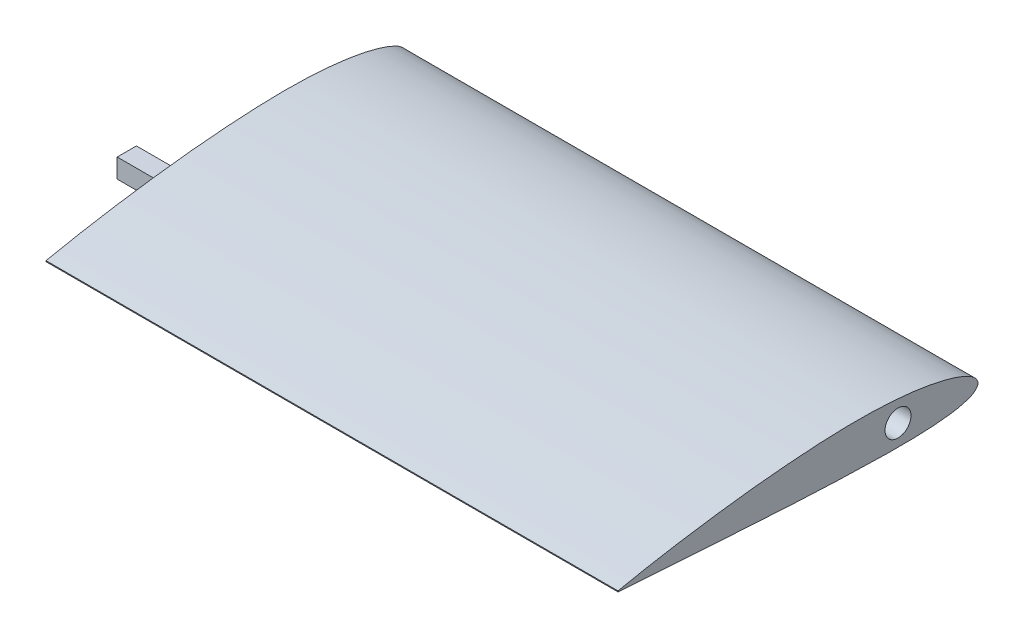
SolidWorks part; units mm, degrees
ref_plane "Front Plane" through (0, 0, 0) normal (0, 0, 1) x (1, 0, 0)
ref_plane "Top Plane" through (0, 0, 0) normal (0, 1, 0) x (1, 0, 0)
ref_plane "Right Plane" through (0, 0, 0) normal (1, 0, 0) x (0, 0, -1)
sketch "Sketch4" plane through (0, 0, 0) normal (0, 0, 1) x (1, 0, 0)
  line L0 (-30.3109, 17.5) -> (30.3109, 17.5)
  arc A1 (30.3109, 17.5) -> (-30.3109, 17.5) centre (0, 0) ccw
  dimension "D1" = 35
  dimension "D2" = 17.5
extrude "Exterior" add sketch "Sketch4" along normal blind 90 contours L0 A1
sketch "Sketch5" plane through (0, 0, 0) normal (0, 0, -1) x (-1, 0, 0)
  line L0 (30.3109, 17.5) -> (-30.3109, 17.5) construction
  line L1 (23.1247, 17.5) -> (-23.1247, 17.5)
  arc A0 (23.1247, 17.5) -> (-23.1247, 17.5) centre (0, 0) ccw
  dimension "D1" = 58
extrude "Boss-Extrude1" add sketch "Sketch5" along normal blind 15
curve "Curve3"
  spline degree 3 poles (0, 1.3, 1000) (0, 4.7133, 983.3426) (0, 11.531, 950.0715) (0, 24.0186, 883.4722) (0, 37.8548, 800.1781) (0, 52.175, 700.1592) (0, 64.1175, 600.1567) (0, 72.8619, 500.1109) (0, 78.7837, 400.0878) (0, 79.786, 316.6355) (0, 77.0249, 249.9395) (0, 72.979, 199.8766) (0, 66.5721, 149.7505) (0, 58.6825, 108.0331) (0, 49.7566, 74.7751) (0, 41.6416, 49.5609) (0, 32.1864, 28.1982) (0, 20.723, 9.771) (0, 0.8988, -6.2982) (0, -16.5264, 10.3934) (0, -24.4739, 28.476) (0, -30.5108, 49.7447) (0, -34.8393, 74.8759) (0, -38.5332, 108.2669) (0, -41.3764, 149.947) (0, -42.5163, 199.9941) (0, -42.3574, 250.0055) (0, -40.8857, 316.6783) (0, -38.2375, 400.0272) (0, -33.6287, 500.0334) (0, -27.6385, 600.0106) (0, -21.4122, 700.0048) (0, -15.1098, 800.0161) (0, -9.3053, 883.3314) (0, -4.8282, 950.0042) (0, -2.4761, 983.334) (0, -1.3, 1000) knots 0 0 0 0 0.025012 0.049959 0.099673 0.149206 0.198581 0.247805 0.296917 0.345953 0.370492 0.395091 0.419815 0.444799 0.45749 0.470406 0.483879 0.491264 0.503459 0.513609 0.520451 0.533235 0.545691 0.558032 0.582609 0.607135 0.631652 0.656174 0.705234 0.75432 0.803437 0.852566 0.901701 0.950849 0.975423 1 1 1 1
sketch "Sketch7" plane through (0, 0, 0) normal (1, 0, 0) x (0, 0, -1)
  line L0 (-90, 21.4324) -> (-90, 21.1984)
  line L1 (-90, 21.3154) -> (0, 21.434) construction
  line L2 (0, 21.434) -> (-0.0572, 64.8516) construction
  line L7 (-90, 17.5) -> (0, 17.5) construction
  line L9 (0, 17.5) -> (0, 29) construction
  spline S1 degree 3 poles (-90, 21.4324) (-88.5009, 21.7395) (-85.5067, 22.3531) (-79.5132, 23.4769) (-72.0173, 24.7221) (-63.0162, 26.0108) (-54.0165, 27.0856) (-45.013, 27.8725) (-36.0116, 28.4054) (-28.5014, 28.4956) (-22.4991, 28.2471) (-17.9938, 27.883) (-13.4827, 27.3065) (-9.7284, 26.5964) (-6.7354, 25.7932) (-4.4663, 25.0629) (-2.5438, 24.212) (-0.8854, 23.1803) (0.5607, 21.3963) (-0.9415, 19.8281) (-2.5688, 19.1129) (-4.4828, 18.5696) (-6.7445, 18.18) (-9.7495, 17.8476) (-13.5004, 17.5918) (-18.0044, 17.4892) (-22.5051, 17.5035) (-28.5052, 17.6359) (-36.0061, 17.8742) (-45.0061, 18.289) (-54.0034, 18.8281) (-63.0023, 19.3884) (-72.0027, 19.9556) (-79.5005, 20.478) (-85.5007, 20.8809) (-88.5002, 21.0925) (-90, 21.1984) knots 0 0 0 0 0.025012 0.049959 0.099673 0.149206 0.198581 0.247805 0.296917 0.345953 0.370492 0.395091 0.419815 0.444799 0.45749 0.470406 0.483879 0.491264 0.503459 0.513609 0.520451 0.533235 0.545691 0.558032 0.582609 0.607135 0.631652 0.656174 0.705234 0.75432 0.803437 0.852566 0.901701 0.950849 0.975423 1 1 1 1
  dimension "D1" = 90
ref_plane "Plane1" through (80, 0, 0) normal (1, 0, 0) x (0, 0, -1)
ref_plane "Plane2" through (-80, 0, 0) normal (1, 0, 0) x (0, 0, -1)
sketch "Sketch8" plane through (80, 0, 0) normal (1, 0, 0) x (0, 0, -1)
  line L0 (-90, 21.4324) -> (-90, 21.1984)
  spline S0 degree 3 poles (-716.115, 1915.3026) (-242.1094, -47.4437) (-166.1672, 7.229) (-79.5132, 23.4769) (-72.0173, 24.7221) (-63.0162, 26.0108) (-54.0165, 27.0856) (-45.013, 27.8725) (-36.0116, 28.4054) (-28.5014, 28.4956) (-22.4991, 28.2471) (-17.9938, 27.883) (-13.4827, 27.3065) (-9.7284, 26.5964) (-6.7354, 25.7932) (-4.4663, 25.0629) (-2.5438, 24.212) (-0.8854, 23.1803) (0.5607, 21.3963) (-0.9415, 19.8281) (-2.5688, 19.1129) (-4.4828, 18.5696) (-6.7445, 18.18) (-9.7495, 17.8476) (-13.5004, 17.5918) (-18.0044, 17.4892) (-22.5051, 17.5035) (-28.5052, 17.6359) (-36.0061, 17.8742) (-45.0061, 18.289) (-54.0034, 18.8281) (-63.0023, 19.3884) (-72.0027, 19.9556) (-79.5005, 20.478) (-222.3619, 30.0711) (-360.6967, 61.6518) (-633.8387, -1888.1939) knots -1.34139 -1.34139 -1.34139 -1.34139 0.025012 0.049959 0.099673 0.149206 0.198581 0.247805 0.296917 0.345953 0.370492 0.395091 0.419815 0.444799 0.45749 0.470406 0.483879 0.491264 0.503459 0.513609 0.520451 0.533235 0.545691 0.558032 0.582609 0.607135 0.631652 0.656174 0.705234 0.75432 0.803437 0.852566 0.901701 0.950849 0.975423 3.242166 3.242166 3.242166 3.242166 only from (-90, 21.4324) to (-90, 21.1984) construction
  spline S1 degree 3 poles (-90, 21.4324) (-88.5009, 21.7395) (-85.5067, 22.3531) (-79.5132, 23.4769) (-72.0173, 24.7221) (-63.0162, 26.0108) (-54.0165, 27.0856) (-45.013, 27.8725) (-36.0116, 28.4054) (-28.5014, 28.4956) (-22.4991, 28.2471) (-17.9938, 27.883) (-13.4827, 27.3065) (-9.7284, 26.5964) (-6.7354, 25.7932) (-4.4663, 25.0629) (-2.5438, 24.212) (-0.8854, 23.1803) (0.5607, 21.3963) (-0.9415, 19.8281) (-2.5688, 19.1129) (-4.4828, 18.5696) (-6.7445, 18.18) (-9.7495, 17.8476) (-13.5004, 17.5918) (-18.0044, 17.4892) (-22.5051, 17.5035) (-28.5052, 17.6359) (-36.0061, 17.8742) (-45.0061, 18.289) (-54.0034, 18.8281) (-63.0023, 19.3884) (-72.0027, 19.9556) (-79.5005, 20.478) (-85.5007, 20.8809) (-88.5002, 21.0925) (-90, 21.1984) knots 0 0 0 0 0.025012 0.049959 0.099673 0.149206 0.198581 0.247805 0.296917 0.345953 0.370492 0.395091 0.419815 0.444799 0.45749 0.470406 0.483879 0.491264 0.503459 0.513609 0.520451 0.533235 0.545691 0.558032 0.582609 0.607135 0.631652 0.656174 0.705234 0.75432 0.803437 0.852566 0.901701 0.950849 0.975423 1 1 1 1
sketch "Sketch9" plane through (-80, 0, 0) normal (1, 0, 0) x (0, 0, -1)
  line L0 (-90, 21.4324) -> (-90, 21.1984)
  spline S0 degree 3 poles (-716.115, 1915.3026) (-242.1094, -47.4437) (-166.1672, 7.229) (-79.5132, 23.4769) (-72.0173, 24.7221) (-63.0162, 26.0108) (-54.0165, 27.0856) (-45.013, 27.8725) (-36.0116, 28.4054) (-28.5014, 28.4956) (-22.4991, 28.2471) (-17.9938, 27.883) (-13.4827, 27.3065) (-9.7284, 26.5964) (-6.7354, 25.7932) (-4.4663, 25.0629) (-2.5438, 24.212) (-0.8854, 23.1803) (0.5607, 21.3963) (-0.9415, 19.8281) (-2.5688, 19.1129) (-4.4828, 18.5696) (-6.7445, 18.18) (-9.7495, 17.8476) (-13.5004, 17.5918) (-18.0044, 17.4892) (-22.5051, 17.5035) (-28.5052, 17.6359) (-36.0061, 17.8742) (-45.0061, 18.289) (-54.0034, 18.8281) (-63.0023, 19.3884) (-72.0027, 19.9556) (-79.5005, 20.478) (-222.3619, 30.0711) (-360.6967, 61.6518) (-633.8387, -1888.1939) knots -1.34139 -1.34139 -1.34139 -1.34139 0.025012 0.049959 0.099673 0.149206 0.198581 0.247805 0.296917 0.345953 0.370492 0.395091 0.419815 0.444799 0.45749 0.470406 0.483879 0.491264 0.503459 0.513609 0.520451 0.533235 0.545691 0.558032 0.582609 0.607135 0.631652 0.656174 0.705234 0.75432 0.803437 0.852566 0.901701 0.950849 0.975423 3.242166 3.242166 3.242166 3.242166 only from (-90, 21.4324) to (-90, 21.1984) construction
  spline S1 degree 3 poles (-90, 21.4324) (-88.5009, 21.7395) (-85.5067, 22.3531) (-79.5132, 23.4769) (-72.0173, 24.7221) (-63.0162, 26.0108) (-54.0165, 27.0856) (-45.013, 27.8725) (-36.0116, 28.4054) (-28.5014, 28.4956) (-22.4991, 28.2471) (-17.9938, 27.883) (-13.4827, 27.3065) (-9.7284, 26.5964) (-6.7354, 25.7932) (-4.4663, 25.0629) (-2.5438, 24.212) (-0.8854, 23.1803) (0.5607, 21.3963) (-0.9415, 19.8281) (-2.5688, 19.1129) (-4.4828, 18.5696) (-6.7445, 18.18) (-9.7495, 17.8476) (-13.5004, 17.5918) (-18.0044, 17.4892) (-22.5051, 17.5035) (-28.5052, 17.6359) (-36.0061, 17.8742) (-45.0061, 18.289) (-54.0034, 18.8281) (-63.0023, 19.3884) (-72.0027, 19.9556) (-79.5005, 20.478) (-85.5007, 20.8809) (-88.5002, 21.0925) (-90, 21.1984) knots 0 0 0 0 0.025012 0.049959 0.099673 0.149206 0.198581 0.247805 0.296917 0.345953 0.370492 0.395091 0.419815 0.444799 0.45749 0.470406 0.483879 0.491264 0.503459 0.513609 0.520451 0.533235 0.545691 0.558032 0.582609 0.607135 0.631652 0.656174 0.705234 0.75432 0.803437 0.852566 0.901701 0.950849 0.975423 1 1 1 1
loft "Loft9" add profiles "Sketch8", "Sketch9"
sketch "Sketch12" plane through (80, 0, 0) normal (1, 0, 0) x (0, 0, -1)
  line L0 (-90, 21.4324) -> (-90, 21.1984) construction
  line L1 (-90, 21.4324) -> (-90, 21.1984)
  line L2 (-90, 21.4324) -> (-97.2409, 26.9065)
  line L3 (-97.2409, 26.9065) -> (-90.2923, 42.7722)
  line L4 (-90.2923, 42.7722) -> (-30.1138, 44.0233)
  line L5 (-30.1138, 44.0233) -> (6.4186, 38.5184)
  line L6 (6.4186, 38.5184) -> (-0.0113, 30.0134)
  line L7 (0, 21.434) -> (-0.0572, 64.8516) construction
  line L8 (-0.0113, 30.0134) -> (-31.6288, 28.4362)
  spline S0 degree 3 poles (-716.115, 1915.3026) (-242.1094, -47.4437) (-166.1672, 7.229) (-79.5132, 23.4769) (-72.0173, 24.7221) (-63.0162, 26.0108) (-54.0165, 27.0856) (-45.013, 27.8725) (-36.0116, 28.4054) (-28.5014, 28.4956) (-22.4991, 28.2471) (-17.9938, 27.883) (-13.4827, 27.3065) (-9.7284, 26.5964) (-6.7354, 25.7932) (-4.4663, 25.0629) (-2.5438, 24.212) (-0.8854, 23.1803) (0.5607, 21.3963) (-0.9415, 19.8281) (-2.5688, 19.1129) (-4.4828, 18.5696) (-6.7445, 18.18) (-9.7495, 17.8476) (-13.5004, 17.5918) (-18.0044, 17.4892) (-22.5051, 17.5035) (-28.5052, 17.6359) (-36.0061, 17.8742) (-45.0061, 18.289) (-54.0034, 18.8281) (-63.0023, 19.3884) (-72.0027, 19.9556) (-79.5005, 20.478) (-222.3619, 30.0711) (-360.6967, 61.6518) (-633.8387, -1888.1939) knots -1.34139 -1.34139 -1.34139 -1.34139 0.025012 0.049959 0.099673 0.149206 0.198581 0.247805 0.296917 0.345953 0.370492 0.395091 0.419815 0.444799 0.45749 0.470406 0.483879 0.491264 0.503459 0.513609 0.520451 0.533235 0.545691 0.558032 0.582609 0.607135 0.631652 0.656174 0.705234 0.75432 0.803437 0.852566 0.901701 0.950849 0.975423 3.242166 3.242166 3.242166 3.242166 only from (-90, 21.4324) to (-90, 21.1984) construction
  spline S1 degree 3 poles (-90, 21.4324) (-88.5009, 21.7395) (-85.5067, 22.3531) (-79.5132, 23.4769) (-72.0173, 24.7221) (-63.0162, 26.0108) (-54.0165, 27.0856) (-45.013, 27.8725) (-37.5506, 28.3143) (-33.0875, 28.4219) (-31.6288, 28.4362) knots 0 0 0 0 0.025012 0.049959 0.099673 0.149206 0.198581 0.247805 0.296917 0.320756 0.320756 0.320756 0.320756
  spline S2 degree 3 poles (-90, 21.4324) (-88.518, 21.738) (-85.5578, 22.3484) (-79.6323, 23.4671) (-72.2211, 24.7077) (-63.3216, 25.9932) (-54.4234, 27.0671) (-45.5209, 27.8564) (-37.9232, 28.3157) (-33.2903, 28.4252) (-31.6288, 28.4362) knots 0 0 0 0 0.025012 0.049959 0.099673 0.149206 0.198581 0.247805 0.296917 0.324377 0.324377 0.324377 0.324377
extrude "Cut-Extrude1" cut sketch "Sketch12" against normal through all
ref_plane "Plane3" through (0, 30, 0) normal (0, 1, 0) x (1, 0, 0)
sketch "Sketch17" plane through (-80, 0, 0) normal (-1, 0, 0) x (0, 0, 1)
  line L0 (90, 21.4324) -> (90, 21.1984) construction
  line L1 (90, 21.4324) -> (90, 21.1984)
  spline S0 degree 3 poles (716.115, 1915.3026) (242.1094, -47.4437) (166.1672, 7.229) (79.5132, 23.4769) (72.0173, 24.7221) (63.0162, 26.0108) (54.0165, 27.0856) (45.013, 27.8725) (36.0116, 28.4054) (28.5014, 28.4956) (22.4991, 28.2471) (17.9938, 27.883) (13.4827, 27.3065) (9.7284, 26.5964) (6.7354, 25.7932) (4.4663, 25.0629) (2.5438, 24.212) (0.8854, 23.1803) (-0.5607, 21.3963) (0.9415, 19.8281) (2.5688, 19.1129) (4.4828, 18.5696) (6.7445, 18.18) (9.7495, 17.8476) (13.5004, 17.5918) (18.0044, 17.4892) (22.5051, 17.5035) (28.5052, 17.6359) (36.0061, 17.8742) (45.0061, 18.289) (54.0034, 18.8281) (63.0023, 19.3884) (72.0027, 19.9556) (79.5005, 20.478) (222.3619, 30.0711) (360.6967, 61.6518) (633.8387, -1888.1939) knots -1.34139 -1.34139 -1.34139 -1.34139 0.025012 0.049959 0.099673 0.149206 0.198581 0.247805 0.296917 0.345953 0.370492 0.395091 0.419815 0.444799 0.45749 0.470406 0.483879 0.491264 0.503459 0.513609 0.520451 0.533235 0.545691 0.558032 0.582609 0.607135 0.631652 0.656174 0.705234 0.75432 0.803437 0.852566 0.901701 0.950849 0.975423 3.242166 3.242166 3.242166 3.242166 only from (90, 21.4324) to (90, 21.1984) construction
  spline S1 degree 3 poles (90, 21.4324) (88.5009, 21.7395) (85.5067, 22.3531) (79.5132, 23.4769) (72.0173, 24.7221) (63.0162, 26.0108) (54.0165, 27.0856) (45.013, 27.8725) (36.0116, 28.4054) (28.5014, 28.4956) (22.4991, 28.2471) (17.9938, 27.883) (13.4827, 27.3065) (9.7284, 26.5964) (6.7354, 25.7932) (4.4663, 25.0629) (2.5438, 24.212) (0.8854, 23.1803) (-0.5607, 21.3963) (0.9415, 19.8281) (2.5688, 19.1129) (4.4828, 18.5696) (6.7445, 18.18) (9.7495, 17.8476) (13.5004, 17.5918) (18.0044, 17.4892) (22.5051, 17.5035) (28.5052, 17.6359) (36.0061, 17.8742) (45.0061, 18.289) (54.0034, 18.8281) (63.0023, 19.3884) (72.0027, 19.9556) (79.5005, 20.478) (85.5007, 20.8809) (88.5002, 21.0925) (90, 21.1984) knots 0 0 0 0 0.025012 0.049959 0.099673 0.149206 0.198581 0.247805 0.296917 0.345953 0.370492 0.395091 0.419815 0.444799 0.45749 0.470406 0.483879 0.491264 0.503459 0.513609 0.520451 0.533235 0.545691 0.558032 0.582609 0.607135 0.631652 0.656174 0.705234 0.75432 0.803437 0.852566 0.901701 0.950849 0.975423 1 1 1 1
extrude "Boss-Extrude2" add sketch "Sketch17" along normal blind 143
ref_plane "Plane5" through (-165, 0, 0) normal (1, 0, 0) x (0, 0, -1)
ref_plane "Plane6" through (-80, 0, 0) normal (1, 0, 0) x (0, 0, -1)
sketch "Sketch18" plane through (-80, 0, 0) normal (1, 0, 0) x (0, 0, -1)
  line L0 (-99.867, 5.7154) -> (-104.3901, 63.3258)
  line L1 (-104.3901, 63.3258) -> (31.8989, 60.8261)
  line L2 (31.8989, 60.8261) -> (39.2788, -3.2119)
  line L3 (39.2788, -3.2119) -> (-99.867, 5.7154)
extrude "Cut-Extrude6" cut sketch "Sketch18" along normal through all
sketch "Sketch13" plane through (-80, 0, 0) normal (-1, 0, 0) x (0, 0, 1)
  line L0 (20, 17.5001) -> (20, 28.0366) construction
  circle A0 centre (20, 22.7683) radius 3.25
  spline S0 degree 3 poles (90, 21.4324) (88.5009, 21.7395) (85.5067, 22.3531) (79.5132, 23.4769) (72.0173, 24.7221) (63.0162, 26.0108) (54.0165, 27.0856) (45.013, 27.8725) (36.0116, 28.4054) (28.5014, 28.4956) (22.4991, 28.2471) (17.9938, 27.883) (13.4827, 27.3065) (9.7284, 26.5964) (6.7354, 25.7932) (4.4663, 25.0629) (2.5438, 24.212) (0.8854, 23.1803) (-0.5607, 21.3963) (0.9415, 19.8281) (2.5688, 19.1129) (4.4828, 18.5696) (6.7445, 18.18) (9.7495, 17.8476) (13.5004, 17.5918) (18.0044, 17.4892) (22.5051, 17.5035) (28.5052, 17.6359) (36.0061, 17.8742) (45.0061, 18.289) (54.0034, 18.8281) (63.0023, 19.3884) (72.0027, 19.9556) (79.5005, 20.478) (85.5007, 20.8809) (88.5002, 21.0925) (90, 21.1984) knots 0 0 0 0 0.025012 0.049959 0.099673 0.149206 0.198581 0.247805 0.296917 0.345953 0.370492 0.395091 0.419815 0.444799 0.45749 0.470406 0.483879 0.491264 0.503459 0.513609 0.520451 0.533235 0.545691 0.558032 0.582609 0.607135 0.631652 0.656174 0.705234 0.75432 0.803437 0.852566 0.901701 0.950849 0.975423 1 1 1 1 construction
  point P8 (20, 22.7683)
  dimension "D1" = 6.5
  dimension "D2" = 20
extrude "Cut-Extrude2" cut sketch "Sketch13" against normal through all and the other way through all
sketch "Sketch19" plane through (-223, 0, 0) normal (-1, 0, 0) x (0, 0, 1)
  line L0 (57.6, 25.1683) -> (62.4, 25.1683)
  line L1 (62.4, 25.1683) -> (62.4, 20.3683)
  line L2 (62.4, 20.3683) -> (57.6, 20.3683)
  line L3 (57.6, 20.3683) -> (57.6, 25.1683)
  line L4 (20, 22.7683) -> (28.325, 22.7683) construction
  circle A0 centre (20, 22.7683) radius 3.25 construction
  point P6 (60, 25.1683)
  point P11 (57.6, 22.7683)
  dimension "D3" = 40
  dimension "D1" = 4.8
  dimension "D2" = 4.8
extrude "Boss-Extrude3" add sketch "Sketch19" along normal blind 9.8
equation "\"fuse_diam\"= 0.07"
equation "\"fuse_rad\"= 0.035"
equation "\"battery_length\"= 0.076"
equation "\"battery_width\"= 0.034"
equation "\"battery_height\"= 0.051"
equation "\"bat_bay_length\"= 0.096"
equation "\"shell\"= 0.002"
equation "\"D1@Exterior\"=\"chord_length\""
equation "\"wing_shelf\"= 0.0175"
equation "\"chord_length\"= 0.09"
equation "\"tail_length\"= 0.26598000000000005"
equation "\"tail_diam\"= 0.035"
equation "\"connector\"= 0.06649500000000001"
equation "\"D2@Sketch4\"=\"wing_shelf\""
equation "\"D1@Sketch4\"=\"fuse_rad\""
equation "\"D1@Sketch5\"=\"fuse_diam\"-0.012"
equation "\"D1@Sketch7\"=\"chord_length\""
equation "\"D3@Sketch20\"=\"chord_length\"/5"
